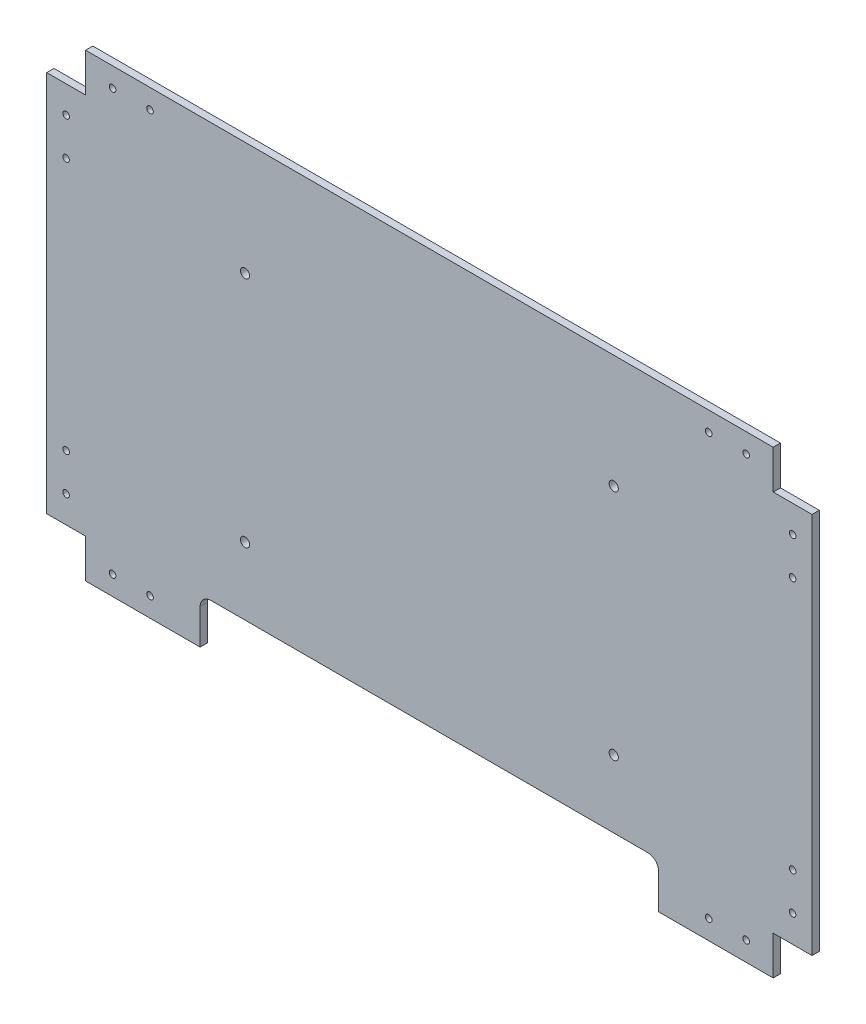
SolidWorks part; units mm, degrees
ref_plane "前基準面" through (0, 0, 0) normal (0, 0, 1) x (1, 0, 0)
ref_plane "上基準面" through (0, 0, 0) normal (0, 1, 0) x (1, 0, 0)
ref_plane "右基準面" through (0, 0, 0) normal (1, 0, 0) x (0, 0, -1)
sketch "草圖1" plane through (0, 0, 0) normal (0, 0, 1) x (1, 0, 0)
  line L1 (-250.4, 150.4) -> (250.4, 150.4)
  line L2 (-250.4, 150.4) -> (-250.4, -150.4)
  line L3 (-250.4, -150.4) -> (250.4, -150.4)
  line L4 (250.4, 150.4) -> (250.4, -150.4)
  line L5 (-250.4, 150.4) -> (250.4, -150.4) construction
  line L6 (-250.4, -150.4) -> (250.4, 150.4) construction
  point P0 (0, 0)
  dimension "D1" = 500.8
  dimension "D2" = 300.8
extrude "填料-伸長1" add sketch "草圖1" along normal blind 4.75 contours L1 L4 L3 L2
sketch "草圖2" plane through (0, 0, 0) normal (0, 0, -1) x (-1, 0, 0)
  line L0 (-120.65, 76.2) -> (-120.65, -76.2) construction
  line L1 (-250.4, 150.4) -> (-225, 150.4)
  line L2 (-250.4, 150.4) -> (-250.4, 125)
  line L3 (-250.4, 125) -> (-225, 125)
  line L4 (-225, 150.4) -> (-225, 125)
  line L5 (-250.4, -150.4) -> (-225, -150.4)
  line L6 (-250.4, -150.4) -> (-250.4, -125)
  line L7 (-250.4, -125) -> (-225, -125)
  line L8 (-225, -150.4) -> (-225, -125)
  line L9 (250.4, 150.4) -> (225, 150.4)
  line L10 (250.4, 150.4) -> (250.4, 125)
  line L11 (250.4, 125) -> (225, 125)
  line L12 (225, 150.4) -> (225, 125)
  line L13 (250.4, -150.4) -> (225, -150.4)
  line L14 (250.4, -150.4) -> (250.4, -125)
  line L15 (250.4, -125) -> (225, -125)
  line L16 (225, -150.4) -> (225, -125)
  line L17 (-120.65, -76.2) -> (120.65, -76.2) construction
  line L18 (120.65, 76.2) -> (120.65, -76.2) construction
  line L20 (120.65, 76.2) -> (-120.65, 76.2) construction
  line L23 (-120.65, 76.2) -> (120.65, -76.2) construction
  line L24 (120.65, -76.2) -> (120.65, 76.2) construction
  line L25 (120.65, 76.2) -> (-120.65, -76.2) construction
  line L27 (250.4, 150.4) -> (-250.4, 150.4) construction
  line L33 (-50, -72.85) -> (50, -112.85) construction
  line L34 (-50, -112.85) -> (50, -72.85) construction
  line L36 (-250.4, 150.4) -> (-250.4, -150.4) construction
  circle A0 centre (-120.65, 76.2) radius 3
  circle A1 centre (-120.65, -76.2) radius 3
  circle A2 centre (120.65, -76.2) radius 3
  circle A3 centre (120.65, 76.2) radius 3
  point P30 (0, 150.4)
  point P31 (0, 0)
  point P32 (0, -92.85)
  point P41 (-250.4, 0)
  dimension "D10" = 6
  dimension "D11" = 6
  dimension "D12" = 6
  dimension "D13" = 6
  dimension "D1" = 25.4
  dimension "D2" = 25.4
  dimension "D3" = 25.4
  dimension "D4" = 25.4
  dimension "D5" = 25.4
  dimension "D6" = 25.4
  dimension "D7" = 25.4
  dimension "D8" = 25.4
  dimension "D9" = 152.4
  dimension "D14" = 241.3
  dimension "D17" = 40
  dimension "D18" = 100
extrude "除料-伸長1" cut sketch "草圖2" against normal blind 10
sketch "草圖3" plane through (0, 0, 4.75) normal (0, 0, 1) x (1, 0, 0)
  circle A0 centre (207.3, 137.7) radius 2.15
  circle A1 centre (182.8, 137.7) radius 2.15
extrude "除料-伸長2" cut sketch "草圖3" against normal blind 5
sketch "草圖4" plane through (0, 0, 4.75) normal (0, 0, 1) x (1, 0, 0)
  circle A0 centre (237.7, 82.8) radius 2.15
  circle A1 centre (237.7, 107.3) radius 2.15
extrude "除料-伸長3" cut sketch "草圖4" against normal blind 5
sketch "草圖5" plane through (0, 0, 4.75) normal (0, 0, 1) x (1, 0, 0)
  circle A0 centre (237.7, -107.3) radius 2.15
  circle A1 centre (237.7, -82.8) radius 2.15
  circle A2 centre (207.3, -137.7) radius 2.15
  circle A3 centre (182.8, -137.7) radius 2.15
extrude "除料-伸長4" cut sketch "草圖5" against normal blind 5
sketch "草圖7" plane through (0, 0, 4.75) normal (0, 0, 1) x (1, 0, 0)
  circle A0 centre (-182.8, -137.7) radius 2.15
  circle A1 centre (-207.3, -137.7) radius 2.15
  circle A2 centre (-237.7, -107.3) radius 2.15
  circle A3 centre (-237.7, -82.8) radius 2.15
  circle A4 centre (-237.7, 82.8) radius 2.15
  circle A5 centre (-237.7, 107.3) radius 2.15
  circle A6 centre (-207.3, 137.7) radius 2.15
  circle A7 centre (-182.8, 137.7) radius 2.15
extrude "除料-伸長6" cut sketch "草圖7" against normal blind 5
sketch "草圖8" plane through (0, 0, 0) normal (0, 0, -1) x (-1, 0, 0)
  line L0 (225, -150.4) -> (-225, -150.4) construction
  line L1 (-150, -150.4) -> (150, -150.4)
  line L2 (-150, -150.4) -> (-150, -120.4)
  line L3 (-150, -120.4) -> (150, -120.4)
  line L4 (150, -150.4) -> (150, -120.4)
  line L5 (-225, -150.4) -> (-225, -125) construction
  dimension "D1" = 300
  dimension "D2" = 30
  dimension "D3" = 75
extrude "除料-伸長7" cut sketch "草圖8" against normal blind 10
fillet "圓角2" radius 7 2 edges at (-150, -120.4, 2.375) (150, -120.4, 2.375)
